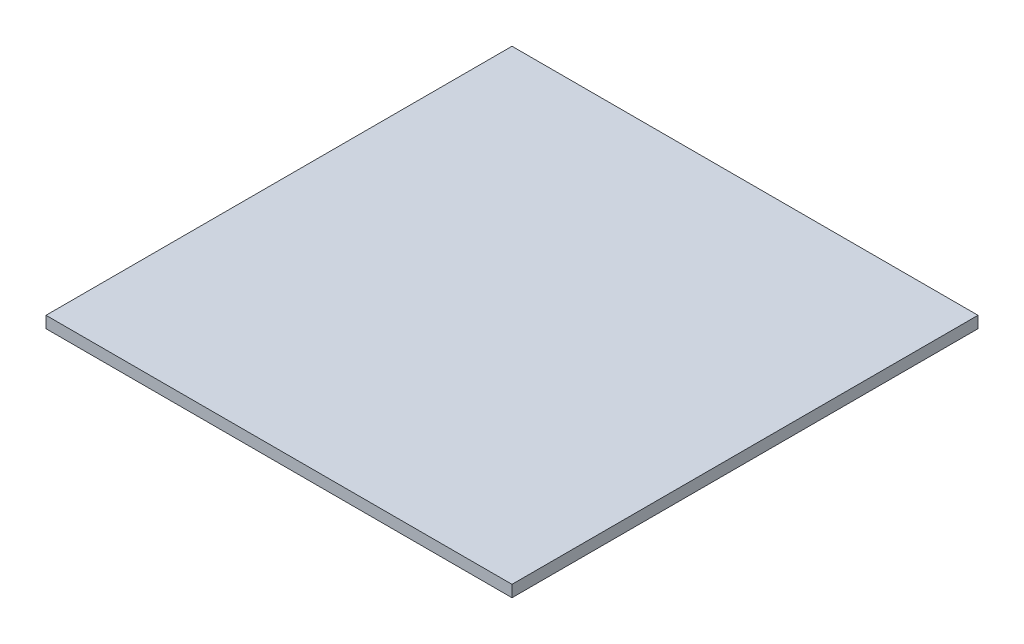
SolidWorks part; units mm, degrees
ref_plane "Front Plane" through (0, 0, 0) normal (0, 0, 1) x (1, 0, 0)
ref_plane "Top Plane" through (0, 0, 0) normal (0, 1, 0) x (1, 0, 0)
ref_plane "Right Plane" through (0, 0, 0) normal (1, 0, 0) x (0, 0, -1)
sketch "Sketch1" plane through (0, 0, 0) normal (0, 1, 0) x (1, 0, 0)
  line L1 (200, -200) -> (-200, -200)
  line L2 (200, -200) -> (200, 200)
  line L3 (200, 200) -> (-200, 200)
  line L4 (-200, -200) -> (-200, 200)
  line L5 (200, -200) -> (-200, 200) construction
  line L6 (200, 200) -> (-200, -200) construction
  point P0 (0, 0)
  dimension "D1" = 400
  dimension "D2" = 400
extrude "Boss-Extrude1" add sketch "Sketch1" along normal blind 10
